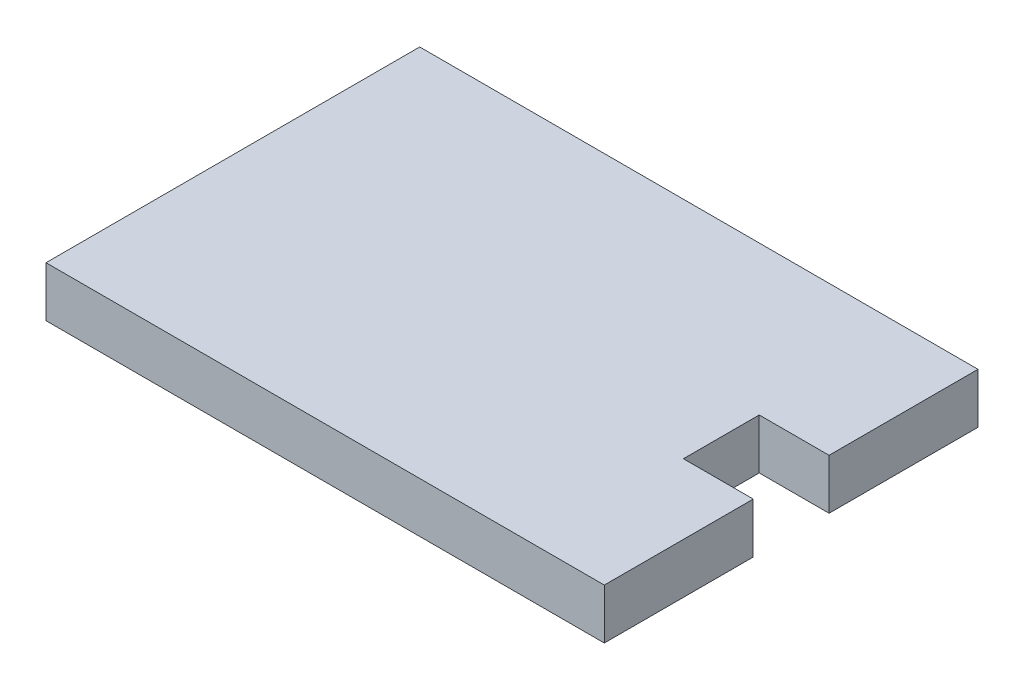
SolidWorks part; units mm, degrees
ref_plane "前视基准面" through (0, 0, 0) normal (0, 0, 1) x (1, 0, 0)
ref_plane "上视基准面" through (0, 0, 0) normal (0, 1, 0) x (1, 0, 0)
ref_plane "右视基准面" through (0, 0, 0) normal (1, 0, 0) x (0, 0, -1)
other "Configuration Table"
sketch "草图1" plane through (0, 0, 0) normal (0, 1, 0) x (1, 0, 0)
  line L0 (0, 0) -> (75.01, 0) construction
  line L1 (-100.04, 66.96) -> (100.04, 66.96)
  line L2 (-100.04, 66.96) -> (-100.04, -66.96)
  line L3 (-100.04, -66.96) -> (100.04, -66.96)
  line L4 (100.04, 66.96) -> (100.04, 13.59)
  line L5 (-100.04, 66.96) -> (100.04, -66.96) construction
  line L6 (-100.04, -66.96) -> (100.04, 66.96) construction
  line L7 (100.04, -13.59) -> (100.04, -66.96)
  line L8 (75.01, 13.59) -> (100.04, 13.59)
  line L9 (75.01, 13.59) -> (75.01, -13.59)
  line L10 (75.01, -13.59) -> (100.04, -13.59)
  point P0 (0, 0)
  point P7 (0, 0)
  point P13 (0, 0)
  dimension "D1" = 133.92
  dimension "D2" = 200.08
  dimension "D3" = 25.03
  dimension "D4" = 27.18
  dimension "D5" = 13.59
extrude "凸台-拉伸1" add sketch "草图1" along normal blind 18
